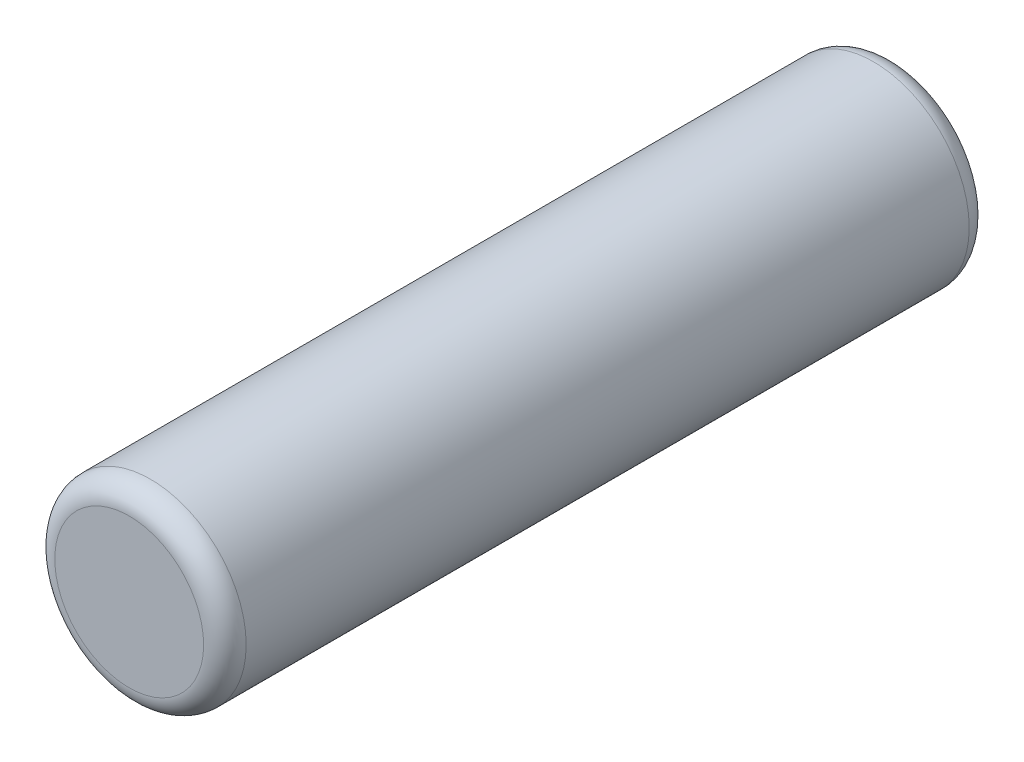
SolidWorks part; units mm, degrees
ref_plane "Plan de face" through (0, 0, 0) normal (0, 0, 1) x (1, 0, 0)
ref_plane "Plan de dessus" through (0, 0, 0) normal (0, 1, 0) x (1, 0, 0)
ref_plane "Plan de droite" through (0, 0, 0) normal (1, 0, 0) x (0, 0, -1)
sketch "Esquisse1" plane through (0, 0, 0) normal (0, 0, 1) x (1, 0, 0)
  circle A0 centre (0, 0) radius 57.15
  dimension "D1" = 114.3
extrude "Boss.-Extru.1" add sketch "Esquisse1" along normal blind 457.2
fillet "Congé1" radius 12.7 2 edges at (57.15, 0, 0) (57.15, 0, 457.2)
